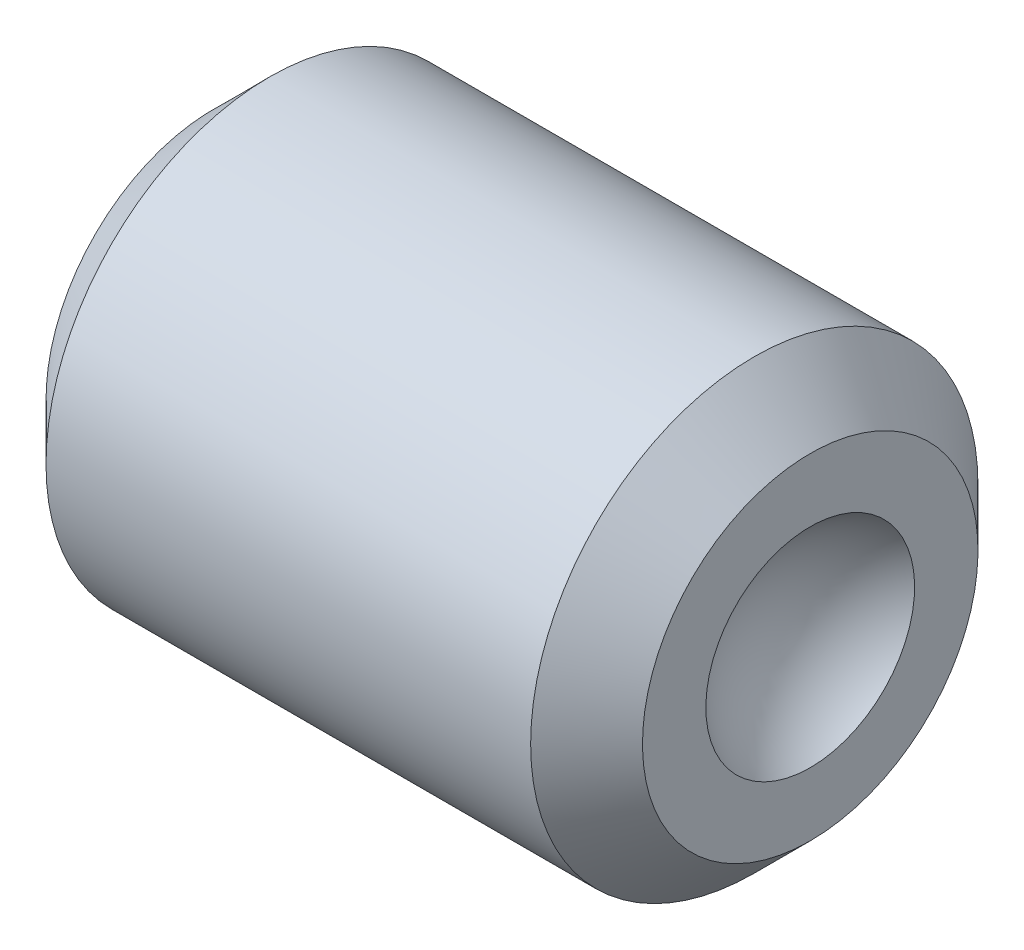
SolidWorks part; units mm, degrees
ref_plane "Front Plane" through (0, 0, 0) normal (0, 0, 1) x (1, 0, 0)
ref_plane "Top Plane" through (0, 0, 0) normal (0, 1, 0) x (1, 0, 0)
ref_plane "Right Plane" through (0, 0, 0) normal (1, 0, 0) x (0, 0, -1)
sketch "Sketch1" plane through (0, 0, 0) normal (0, 0, 1) x (1, 0, 0)
  line L0 (0, 0) -> (0, 1.125)
  line L1 (0, 1.125) -> (0.375, 1.5)
  line L2 (0.375, 1.5) -> (3.625, 1.5)
  line L3 (3.625, 1.5) -> (4, 1.125)
  line L4 (0, 0) -> (3.625, 0) construction
  line L5 (0.375, 1.5) -> (0.375, 1.125) construction
  line L6 (0.375, 1.125) -> (0.375, 0.75) construction
  line L7 (0.375, 0.75) -> (0.375, 0.375) construction
  line L8 (0.375, 0.375) -> (0.375, 0) construction
  line L9 (0.375, 1.125) -> (0, 1.125) construction
  line L10 (3.625, 1.5) -> (3.625, 0) construction
  line L11 (4, 1.125) -> (4, 0.7)
  line L12 (0, 0) -> (3.625, 0)
  arc A0 (3.625, 0) -> (4, 0.7) centre (4.4658, 0) cw
  dimension "D1" = 45
  dimension "D2" = 3
  dimension "D3" = 4
  dimension "D4" = 1.4
revolve "Revolve1" add sketch "Sketch1" angle 360 about L12
sketch "Sketch2" plane through (0, 0, 0) normal (-1, 0, 0) x (0, 0, 1)
  line L1 (0, 0.866) -> (-0.75, 0.433)
  line L2 (-0.75, 0.433) -> (-0.75, -0.433)
  line L3 (-0.75, -0.433) -> (0, -0.866)
  line L4 (0, -0.866) -> (0.75, -0.433)
  line L5 (0.75, -0.433) -> (0.75, 0.433)
  line L6 (0.75, 0.433) -> (0, 0.866)
  circle A0 centre (0, 0) radius 0.75 construction
  dimension "D1" = 1.5
extrude "Cut-Extrude1" cut sketch "Sketch2" against normal offset from surface (2 mm away) 2 up to face at (4, -1.125, 0)
